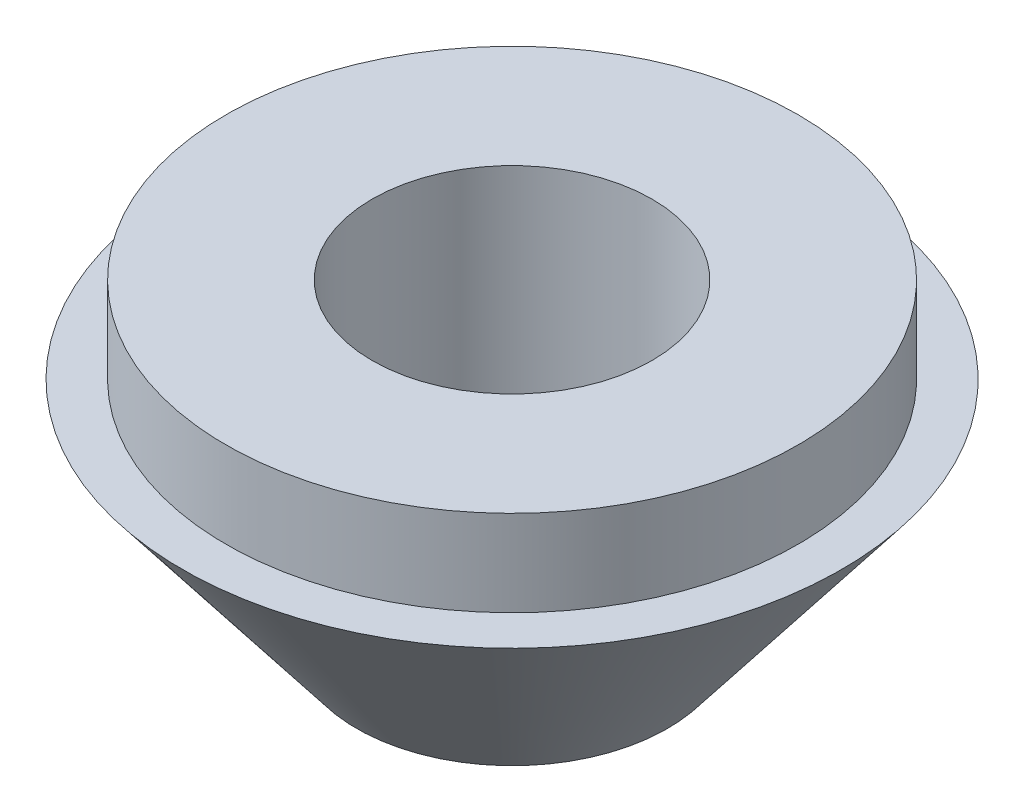
SolidWorks part; units mm, degrees
material "AISI 316 Stainless Steel Sheet (SS)"
ref_plane "Front Plane" through (0, 0, 0) normal (0, 0, 1) x (1, 0, 0)
ref_plane "Top Plane" through (0, 0, 0) normal (0, 1, 0) x (1, 0, 0)
ref_plane "Right Plane" through (0, 0, 0) normal (1, 0, 0) x (0, 0, -1)
sketch "Sketch1" plane through (0, 0, 0) normal (0, 0, 1) x (1, 0, 0)
  line L0 (0, 0) -> (0, 12.7)
  line L1 (0, 12.7) -> (-11.684, 12.7)
  line L2 (-11.684, 12.7) -> (-11.684, 9.1838)
  line L3 (-11.684, 9.1838) -> (-13.462, 9.1838)
  line L4 (-13.462, 9.1838) -> (-6.35, 0)
  line L5 (-6.35, 0) -> (0, 0)
  dimension "D1" = 12.7
  dimension "D2" = 9.1838
  dimension "D3" = 1.778
  dimension "D4" = 6.35
  dimension "D5" = 11.684
revolve "Revolve1" add sketch "Sketch1" angle 360 about L0
sketch "]" plane through (0, 12.7, 0) normal (0, 1, 0) x (1, 0, 0)
  circle A0 centre (0, 0) radius 5.715
  circle A1 centre (0, 0) radius 5.715
  dimension "D1" = 11.43
extrude "Cut-Extrude4" cut sketch "]" against normal blind 12.7 contours A0
